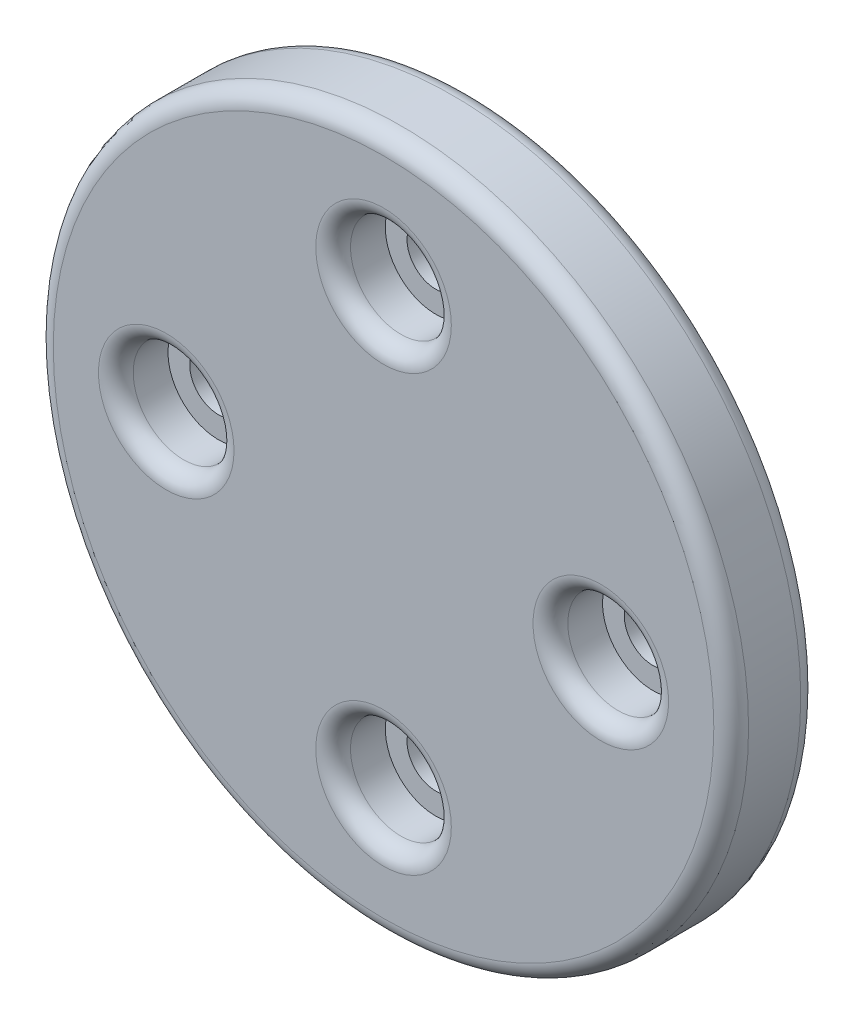
SolidWorks part; units mm, degrees
ref_plane "Ebene vorne" through (0, 0, 0) normal (0, 0, 1) x (1, 0, 0)
ref_plane "Ebene oben" through (0, 0, 0) normal (0, 1, 0) x (1, 0, 0)
ref_plane "Ebene rechts" through (0, 0, 0) normal (1, 0, 0) x (0, 0, -1)
sketch "Skizze1" plane through (0, 0, 0) normal (0, 0, 1) x (1, 0, 0)
  circle A0 centre (0, 0) radius 20
  circle A2 centre (12.5, 0) radius 1.65
  circle A3 centre (0, -12.5) radius 1.65
  circle A4 centre (-12.5, 0) radius 1.65
  circle A5 centre (0, 12.5) radius 1.65
  point P15 (0, 0)
  dimension "D1" = 40
  dimension "D2" = 12.5
  dimension "D3" = 4
  dimension "D4" = 3.3
extrude "Aufsatz-Linear austragen1" add sketch "Skizze1" along normal blind 5
sketch "Skizze2" plane through (0, 0, 5) normal (0, 0, 1) x (1, 0, 0)
  circle A0 centre (0, 12.5) radius 2.9
  circle A1 centre (12.5, 0) radius 2.9
  circle A2 centre (0, -12.5) radius 2.9
  circle A3 centre (-12.5, 0) radius 2.9
  point P3 (0, 0)
  point P12 (0, 0)
  dimension "D1" = 4
  dimension "D2" = 5.8
extrude "Schnitt-Linear austragen1" cut sketch "Skizze2" against normal blind 3
fillet "Verrundung1" radius 1 10 edges at (20, 0, 0) (14.15, 0, 0) (1.65, -12.5, 0) (-10.85, 0, 0) (1.65, 12.5, 0) (20, 0, 5) (-9.6, 0, 5) (2.9, -12.5, 5) (15.4, 0, 5) (2.9, 12.5, 5)
